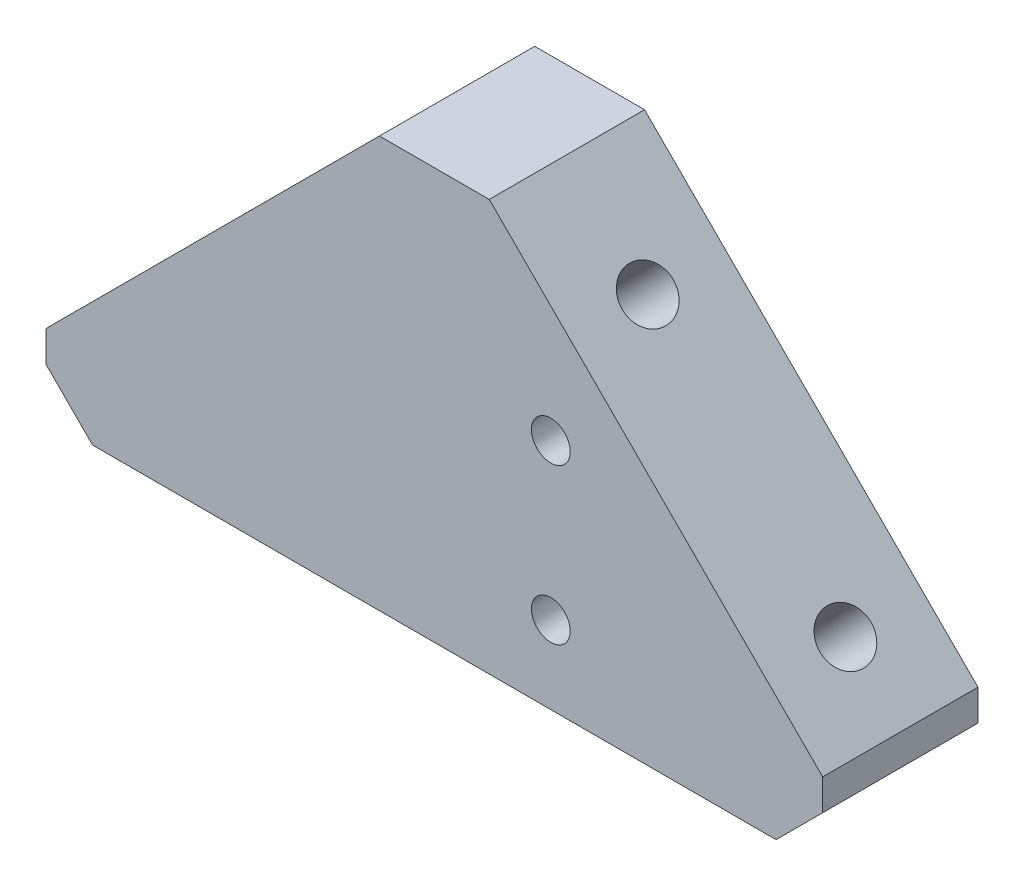
SolidWorks part; units mm, degrees
ref_plane "Front" through (0, 0, 0) normal (0, 0, 1) x (1, 0, 0)
ref_plane "Top" through (0, 0, 0) normal (0, 1, 0) x (1, 0, 0)
ref_plane "Right" through (0, 0, 0) normal (1, 0, 0) x (0, 0, -1)
sketch "Esquisse1" plane through (0, 0, 0) normal (0, 0, 1) x (1, 0, 0)
  line L0 (-25, 0) -> (25, 0)
  line L1 (25, 0) -> (25, 5)
  line L2 (25, 5) -> (0, 30)
  line L3 (0, 30) -> (0, 0) construction
  line L4 (-25, 5) -> (0, 30)
  line L5 (-25, 0) -> (-25, 5)
  point P5 (25, 2.5)
  dimension "D1" = 50
  dimension "D2" = 45
  dimension "D3" = 5
extrude "Boss.-Extru.1" add sketch "Esquisse1" along normal blind 10
sketch "Esquisse2" plane through (15, 15, 0) normal (0.7071, 0.7071, 0) x (0, 0, -1)
  line L0 (-5, -14.1421) -> (-5, 21.2132) construction
  line L1 (-10, -14.1421) -> (0, -14.1421) construction
  line L2 (-10, 21.2132) -> (0, 21.2132) construction
  circle A0 centre (-5, 8.8579) radius 1.65
  circle A1 centre (-5, -9.1421) radius 1.65
  dimension "D1" = 18
  dimension "D2" = 3.3
  dimension "D3" = 5
extrude "Enlèv. mat.-Extru.1" cut sketch "Esquisse2" against normal blind 8
sketch "Esquisse3" plane through (-15, 15, 0) normal (-0.7071, 0.7071, 0) x (0, 0, 1)
  line L0 (5, -14.1421) -> (5, 21.2132) construction
  line L1 (10, -14.1421) -> (0, -14.1421) construction
  line L2 (10, 21.2132) -> (0, 21.2132) construction
  circle A0 centre (5, 9.8579) radius 1.65
  circle A1 centre (5, -8.1421) radius 1.65
  dimension "D1" = 18
  dimension "D2" = 3.3
  dimension "D3" = 6
extrude "Enlèv. mat.-Extru.2" cut sketch "Esquisse3" against normal blind 8
chamfer "Chanfrein1" distance 5 angle 45 1 edges at (0, 30, 5)
sketch "Esquisse4" plane through (0, 0, 0) normal (0, -1, 0) x (1, 0, 0)
  line L0 (-25, 5) -> (25, 5) construction
  line L1 (-25, 10) -> (-25, 0) construction
  line L2 (25, 10) -> (25, 0) construction
  line L3 (0, 5) -> (0, 8.5239) construction
  circle A0 centre (0, 5) radius 1.65
  circle A1 centre (-16, 5) radius 1.65
  circle A2 centre (16, 5) radius 1.65
  dimension "D1" = 3.3
  dimension "D2" = 16
extrude "Enlèv. mat.-Extru.3" cut sketch "Esquisse4" against normal blind 10
chamfer "Chanfrein3" distance 3 angle 45 2 edges at (25, 0, 5) (-25, 0, 5)
sketch "Esquisse5" plane through (0, 0, 10) normal (0, 0, 1) x (1, 0, 0)
  line L0 (7.5, 5) -> (7.5, 15) construction
  line L1 (-22, 0) -> (22, 0) construction
  circle A0 centre (7.5, 15) radius 1.25
  circle A1 centre (7.5, 5) radius 1.25
  point P8 (0, 0)
  dimension "D1" = 2.5
  dimension "D2" = 10
  dimension "D3" = 5
  dimension "D4" = 7.5
extrude "Enlèv. mat.-Extru.4" cut sketch "Esquisse5" against normal through all
